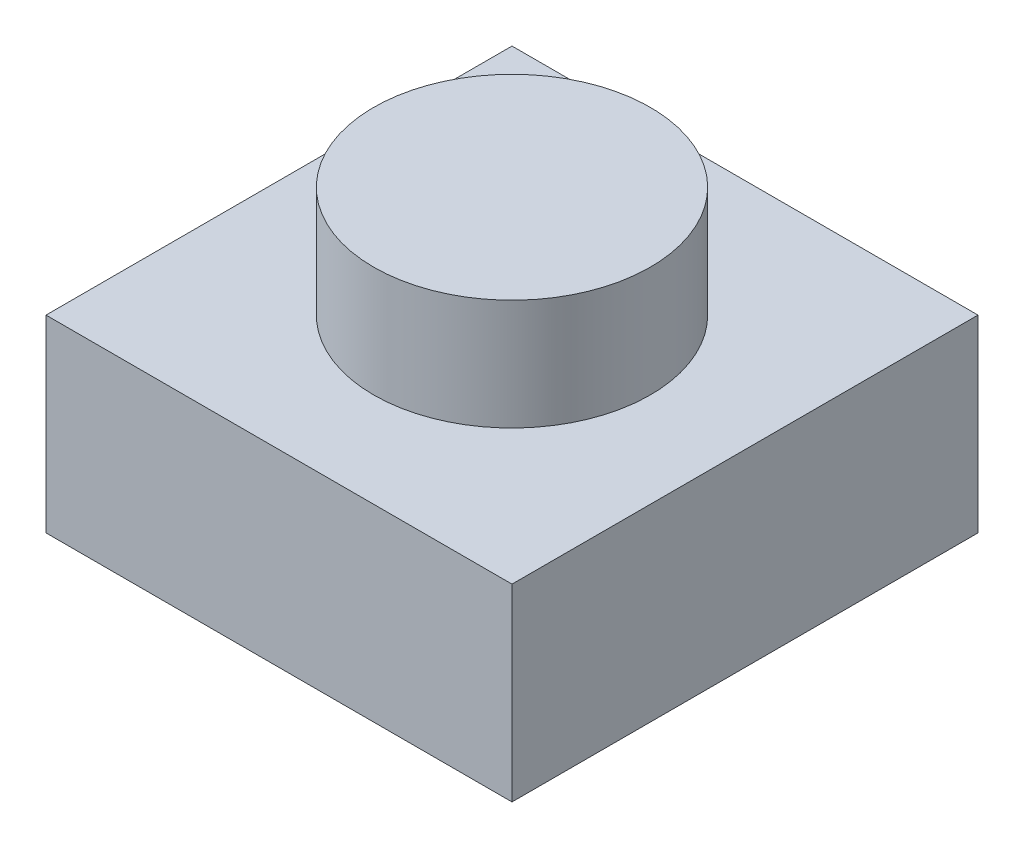
SolidWorks part; units mm, degrees
ref_plane "Front Plane" through (0, 0, 0) normal (0, 0, 1) x (1, 0, 0)
ref_plane "Top Plane" through (0, 0, 0) normal (0, 1, 0) x (1, 0, 0)
ref_plane "Right Plane" through (0, 0, 0) normal (1, 0, 0) x (0, 0, -1)
sketch "Sketch1" plane through (0, 0, 0) normal (0, 1, 0) x (1, 0, 0)
  line L1 (-3.915, 3.915) -> (3.915, 3.915)
  line L2 (-3.915, 3.915) -> (-3.915, -3.915)
  line L3 (-3.915, -3.915) -> (3.915, -3.915)
  line L4 (3.915, 3.915) -> (3.915, -3.915)
  line L5 (-3.915, 3.915) -> (3.915, -3.915) construction
  line L6 (-3.915, -3.915) -> (3.915, 3.915) construction
  point P0 (0, 0)
  dimension "D1" = 7.83
  dimension "D2" = 7.83
extrude "Boss-Extrude1" add sketch "Sketch1" against normal blind 3.17
sketch "Sketch2" plane through (0, 0, 0) normal (0, 1, 0) x (1, 0, 0)
  circle A0 centre (0, 0) radius 2.325
  dimension "D1" = 4.65
extrude "Boss-Extrude2" add sketch "Sketch2" along normal blind 1.86
shell "Shell2" thickness 1.45
